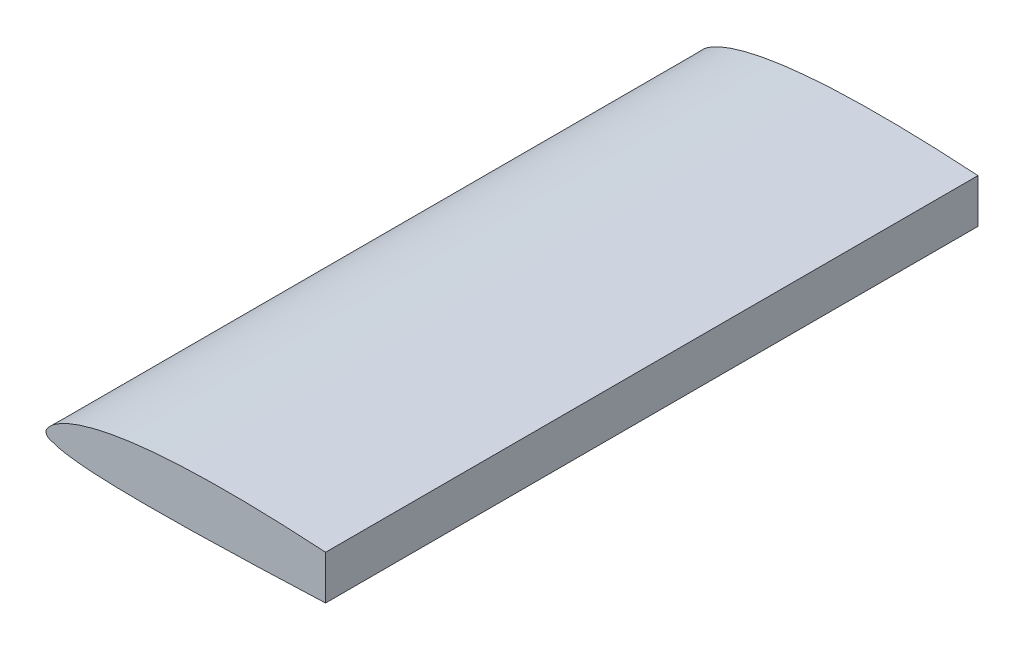
SolidWorks part; units mm, degrees
ref_plane "Front Plane" through (0, 0, 0) normal (0, 0, 1) x (1, 0, 0)
ref_plane "Top Plane" through (0, 0, 0) normal (0, 1, 0) x (1, 0, 0)
ref_plane "Right Plane" through (0, 0, 0) normal (1, 0, 0) x (0, 0, -1)
curve "Curve1"
  spline degree 3 poles (152.4, 0, 0) (152.2328, 0.0185, 0) (151.5718, 0.0917, 0) (150.114, 0.2839, 0) (147.7494, 0.6387, 0) (144.5559, 1.1702, 0) (140.6154, 1.8591, 0) (136.0078, 2.6715, 0) (130.8064, 3.5628, 0) (125.0738, 4.4862, 0) (118.8647, 5.3978, 0) (112.2333, 6.273, 0) (105.2435, 7.1061, 0) (97.9697, 7.8893, 0) (90.4927, 8.6067, 0) (82.8953, 9.2407, 0) (75.2587, 9.7775, 0) (67.6629, 10.1988, 0) (60.1868, 10.4917, 0) (52.9059, 10.6451, 0) (45.8917, 10.6446, 0) (39.2107, 10.4862, 0) (32.9233, 10.1644, 0) (27.0837, 9.6709, 0) (21.7372, 9.0165, 0) (16.9243, 8.2041, 0) (12.6763, 7.2498, 0) (9.0198, 6.1745, 0) (5.9657, 5.002, 0) (3.544, 3.7699, 0) (1.7048, 2.5315, 0) (0.5752, 1.3447, 0) (-0.1707, 0.2031, 0) (0.3376, -1.0018, 0) (1.7929, -1.5467, 0) (3.7942, -2.1772, 0) (6.6434, -2.6439, 0) (10.2161, -3.042, 0) (14.5301, -3.3199, 0) (19.534, -3.4977, 0) (25.1869, -3.5776, 0) (31.4286, -3.5738, 0) (38.1919, -3.4966, 0) (45.4016, -3.3493, 0) (52.9784, -3.1418, 0) (60.8387, -2.8853, 0) (68.895, -2.5879, 0) (77.0574, -2.2589, 0) (85.235, -1.9077, 0) (93.3354, -1.5502, 0) (101.266, -1.1955, 0) (108.9342, -0.8624, 0) (116.2465, -0.5575, 0) (123.1102, -0.3069, 0) (129.4317, -0.1079, 0) (135.1235, 0.028, 0) (140.1036, 0.1089, 0) (144.2994, 0.1399, 0) (147.6448, 0.1242, 0) (150.0834, 0.0865, 0) (151.3998, 0.0403, 0) (151.8986, 0.0229, 0) knots 0 0 0 0 0.001635 0.006466 0.014297 0.024884 0.037944 0.053194 0.070377 0.089257 0.109652 0.131396 0.154295 0.178097 0.202531 0.227329 0.252226 0.276966 0.301297 0.324972 0.347773 0.369494 0.389947 0.408979 0.426466 0.442307 0.456421 0.468774 0.479345 0.488156 0.495223 0.500608 0.504417 0.507344 0.511893 0.518766 0.528062 0.53975 0.553782 0.570059 0.588441 0.608748 0.63075 0.654208 0.678865 0.704451 0.730678 0.757254 0.783883 0.810266 0.836095 0.861073 0.884897 0.907258 0.927856 0.946395 0.962618 0.976286 0.987193 0.995147 1 1 1 1
sketch "Sketch1" plane through (0, 0, 0) normal (0, 0, 1) x (1, 0, 0)
  line L0 (151.8986, 0.0229) -> (152.4, 0)
  line L2 (0, 0) -> (0, 1.9929) construction
  spline S0 degree 3 poles (-13.6531, -1992.4593) (197.8364, 10.3076) (173.4363, -2.7909) (150.114, 0.2839) (147.7494, 0.6387) (144.5559, 1.1702) (140.6154, 1.8591) (136.0078, 2.6715) (130.8064, 3.5628) (125.0738, 4.4862) (118.8647, 5.3978) (112.2333, 6.273) (105.2435, 7.1061) (97.9697, 7.8893) (90.4927, 8.6067) (82.8953, 9.2407) (75.2587, 9.7775) (67.6629, 10.1988) (60.1868, 10.4917) (52.9059, 10.6451) (45.8917, 10.6446) (39.2107, 10.4862) (32.9233, 10.1644) (27.0837, 9.6709) (21.7372, 9.0165) (16.9243, 8.2041) (12.6763, 7.2498) (9.0198, 6.1745) (5.9657, 5.002) (3.544, 3.7699) (1.7048, 2.5315) (0.5752, 1.3447) (-0.1707, 0.2031) (0.3376, -1.0018) (1.7929, -1.5467) (3.7942, -2.1772) (6.6434, -2.6439) (10.2161, -3.042) (14.5301, -3.3199) (19.534, -3.4977) (25.1869, -3.5776) (31.4286, -3.5738) (38.1919, -3.4966) (45.4016, -3.3493) (52.9784, -3.1418) (60.8387, -2.8853) (68.895, -2.5879) (77.0574, -2.2589) (85.235, -1.9077) (93.3354, -1.5502) (101.266, -1.1955) (108.9342, -0.8624) (116.2465, -0.5575) (123.1102, -0.3069) (129.4317, -0.1079) (135.1235, 0.028) (140.1036, 0.1089) (144.2994, 0.1399) (147.6448, 0.1242) (190.703, -0.5421) (231.9179, -27.3192) (328.7943, 1990.768) knots -0.214418 -0.214418 -0.214418 -0.214418 0.001635 0.006466 0.014297 0.024884 0.037944 0.053194 0.070377 0.089257 0.109652 0.131396 0.154295 0.178097 0.202531 0.227329 0.252226 0.276966 0.301297 0.324972 0.347773 0.369494 0.389947 0.408979 0.426466 0.442307 0.456421 0.468774 0.479345 0.488156 0.495223 0.500608 0.504417 0.507344 0.511893 0.518766 0.528062 0.53975 0.553782 0.570059 0.588441 0.608748 0.63075 0.654208 0.678865 0.704451 0.730678 0.757254 0.783883 0.810266 0.836095 0.861073 0.884897 0.907258 0.927856 0.946395 0.962618 0.976286 0.987193 0.995147 1.394988 1.394988 1.394988 1.394988 only from (152.4, 0) to (151.8986, 0.0229) construction
  spline S1 degree 3 poles (152.4, 0) (152.2328, 0.0185) (151.5718, 0.0917) (150.114, 0.2839) (147.7494, 0.6387) (144.5559, 1.1702) (140.6154, 1.8591) (136.0078, 2.6715) (130.8064, 3.5628) (125.0738, 4.4862) (118.8647, 5.3978) (112.2333, 6.273) (105.2435, 7.1061) (97.9697, 7.8893) (90.4927, 8.6067) (82.8953, 9.2407) (75.2587, 9.7775) (67.6629, 10.1988) (60.1868, 10.4917) (52.9059, 10.6451) (45.8917, 10.6446) (39.2107, 10.4862) (32.9233, 10.1644) (27.0837, 9.6709) (21.7372, 9.0165) (16.9243, 8.2041) (12.6763, 7.2498) (9.0198, 6.1745) (5.9657, 5.002) (3.544, 3.7699) (1.7048, 2.5315) (0.5752, 1.3447) (-0.1707, 0.2031) (0.3376, -1.0018) (1.7929, -1.5467) (3.7942, -2.1772) (6.6434, -2.6439) (10.2161, -3.042) (14.5301, -3.3199) (19.534, -3.4977) (25.1869, -3.5776) (31.4286, -3.5738) (38.1919, -3.4966) (45.4016, -3.3493) (52.9784, -3.1418) (60.8387, -2.8853) (68.895, -2.5879) (77.0574, -2.2589) (85.235, -1.9077) (93.3354, -1.5502) (101.266, -1.1955) (108.9342, -0.8624) (116.2465, -0.5575) (123.1102, -0.3069) (129.4317, -0.1079) (135.1235, 0.028) (140.1036, 0.1089) (144.2994, 0.1399) (147.6448, 0.1242) (150.0834, 0.0865) (151.3998, 0.0403) (151.8986, 0.0229) knots 0 0 0 0 0.001635 0.006466 0.014297 0.024884 0.037944 0.053194 0.070377 0.089257 0.109652 0.131396 0.154295 0.178097 0.202531 0.227329 0.252226 0.276966 0.301297 0.324972 0.347773 0.369494 0.389947 0.408979 0.426466 0.442307 0.456421 0.468774 0.479345 0.488156 0.495223 0.500608 0.504417 0.507344 0.511893 0.518766 0.528062 0.53975 0.553782 0.570059 0.588441 0.608748 0.63075 0.654208 0.678865 0.704451 0.730678 0.757254 0.783883 0.810266 0.836095 0.861073 0.884897 0.907258 0.927856 0.946395 0.962618 0.976286 0.987193 0.995147 1 1 1 1
extrude "Boss-Extrude1" add sketch "Sketch1" along normal blind 177.8
sketch "Sketch3" plane through (0, 0, 177.8) normal (0, 0, 1) x (1, 0, 0)
  line L0 (76.2, 9.6986) -> (76.2, -2.2909)
  line L1 (0, 0) -> (0, 3.7038) construction
  line L2 (76.2, 3.7038) -> (0, 3.7038) construction
  line L4 (151.8986, 0.0229) -> (152.4, 0)
  line L5 (151.8986, 0.0229) -> (152.4, 0)
  spline S0 degree 3 poles (152.4, 0) (152.2328, 0.0185) (151.5718, 0.0917) (150.114, 0.2839) (147.7494, 0.6387) (144.5559, 1.1702) (140.6154, 1.8591) (136.0078, 2.6715) (130.8064, 3.5628) (125.0738, 4.4862) (118.8647, 5.3978) (112.2333, 6.273) (105.2435, 7.1061) (97.9697, 7.8893) (90.4927, 8.6067) (82.8953, 9.2407) (75.2587, 9.7775) (67.6629, 10.1988) (60.1868, 10.4917) (52.9059, 10.6451) (45.8917, 10.6446) (39.2107, 10.4862) (32.9233, 10.1644) (27.0837, 9.6709) (21.7372, 9.0165) (16.9243, 8.2041) (12.6763, 7.2498) (9.0198, 6.1745) (5.9657, 5.002) (3.544, 3.7699) (1.7048, 2.5315) (0.5752, 1.3447) (-0.1707, 0.2031) (0.3376, -1.0018) (1.7929, -1.5467) (3.7942, -2.1772) (6.6434, -2.6439) (10.2161, -3.042) (14.5301, -3.3199) (19.534, -3.4977) (25.1869, -3.5776) (31.4286, -3.5738) (38.1919, -3.4966) (45.4016, -3.3493) (52.9784, -3.1418) (60.8387, -2.8853) (68.895, -2.5879) (77.0574, -2.2589) (85.235, -1.9077) (93.3354, -1.5502) (101.266, -1.1955) (108.9342, -0.8624) (116.2465, -0.5575) (123.1102, -0.3069) (129.4317, -0.1079) (135.1235, 0.028) (140.1036, 0.1089) (144.2994, 0.1399) (147.6448, 0.1242) (150.0834, 0.0865) (151.3998, 0.0403) (151.8986, 0.0229) knots 0 0 0 0 0.001635 0.006466 0.014297 0.024884 0.037944 0.053194 0.070377 0.089257 0.109652 0.131396 0.154295 0.178097 0.202531 0.227329 0.252226 0.276966 0.301297 0.324972 0.347773 0.369494 0.389947 0.408979 0.426466 0.442307 0.456421 0.468774 0.479345 0.488156 0.495223 0.500608 0.504417 0.507344 0.511893 0.518766 0.528062 0.53975 0.553782 0.570059 0.588441 0.608748 0.63075 0.654208 0.678865 0.704451 0.730678 0.757254 0.783883 0.810266 0.836095 0.861073 0.884897 0.907258 0.927856 0.946395 0.962618 0.976286 0.987193 0.995147 1 1 1 1 construction
  spline S1 degree 3 poles (152.4, 0) (152.2328, 0.0185) (151.5718, 0.0917) (150.114, 0.2839) (147.7494, 0.6387) (144.5559, 1.1702) (140.6154, 1.8591) (136.0078, 2.6715) (130.8064, 3.5628) (125.0738, 4.4862) (118.8647, 5.3978) (112.2333, 6.273) (105.2435, 7.1061) (97.9697, 7.8893) (90.4927, 8.6067) (82.8953, 9.2407) (75.2587, 9.7775) (67.6629, 10.1988) (60.1868, 10.4917) (52.9059, 10.6451) (45.8917, 10.6446) (39.2107, 10.4862) (32.9233, 10.1644) (27.0837, 9.6709) (21.7372, 9.0165) (16.9243, 8.2041) (12.6763, 7.2498) (9.0198, 6.1745) (5.9657, 5.002) (3.544, 3.7699) (1.7048, 2.5315) (0.5752, 1.3447) (-0.1707, 0.2031) (0.3376, -1.0018) (1.7929, -1.5467) (3.7942, -2.1772) (6.6434, -2.6439) (10.2161, -3.042) (14.5301, -3.3199) (19.534, -3.4977) (25.1869, -3.5776) (31.4286, -3.5738) (38.1919, -3.4966) (45.4016, -3.3493) (52.9784, -3.1418) (60.8387, -2.8853) (68.895, -2.5879) (77.0574, -2.2589) (85.235, -1.9077) (93.3354, -1.5502) (101.266, -1.1955) (108.9342, -0.8624) (116.2465, -0.5575) (123.1102, -0.3069) (129.4317, -0.1079) (135.1235, 0.028) (140.1036, 0.1089) (144.2994, 0.1399) (147.6448, 0.1242) (150.0834, 0.0865) (151.3998, 0.0403) (151.8986, 0.0229) knots 0 0 0 0 0.001635 0.006466 0.014297 0.024884 0.037944 0.053194 0.070377 0.089257 0.109652 0.131396 0.154295 0.178097 0.202531 0.227329 0.252226 0.276966 0.301297 0.324972 0.347773 0.369494 0.389947 0.408979 0.426466 0.442307 0.456421 0.468774 0.479345 0.488156 0.495223 0.500608 0.504417 0.507344 0.511893 0.518766 0.528062 0.53975 0.553782 0.570059 0.588441 0.608748 0.63075 0.654208 0.678865 0.704451 0.730678 0.757254 0.783883 0.810266 0.836095 0.861073 0.884897 0.907258 0.927856 0.946395 0.962618 0.976286 0.987193 0.995147 1 1 1 1 construction
  spline S3 degree 3 poles (-120.0863, -2986.5223) (204.7313, 14.3063) (176.6016, -3.2082) (150.114, 0.2839) (147.7494, 0.6387) (144.5559, 1.1702) (140.6154, 1.8591) (136.0078, 2.6715) (130.8064, 3.5628) (125.0738, 4.4862) (118.8647, 5.3978) (112.2333, 6.273) (105.2435, 7.1061) (97.9697, 7.8893) (90.4927, 8.6067) (82.8953, 9.2407) (75.2587, 9.7775) (67.6629, 10.1988) (60.1868, 10.4917) (52.9059, 10.6451) (45.8917, 10.6446) (39.2107, 10.4862) (32.9233, 10.1644) (27.0837, 9.6709) (21.7372, 9.0165) (16.9243, 8.2041) (12.6763, 7.2498) (9.0198, 6.1745) (5.9657, 5.002) (3.544, 3.7699) (1.7048, 2.5315) (0.5752, 1.3447) (-0.1707, 0.2031) (0.3376, -1.0018) (1.7929, -1.5467) (3.7942, -2.1772) (6.6434, -2.6439) (10.2161, -3.042) (14.5301, -3.3199) (19.534, -3.4977) (25.1869, -3.5776) (31.4286, -3.5738) (38.1919, -3.4966) (45.4016, -3.3493) (52.9784, -3.1418) (60.8387, -2.8853) (68.895, -2.5879) (77.0574, -2.2589) (85.235, -1.9077) (93.3354, -1.5502) (101.266, -1.1955) (108.9342, -0.8624) (116.2465, -0.5575) (123.1102, -0.3069) (129.4317, -0.1079) (135.1235, 0.028) (140.1036, 0.1089) (144.2994, 0.1399) (147.6448, 0.1242) (196.5916, -0.6332) (243.4783, -35.3543) (374.0575, 2989.6631) knots -0.245458 -0.245458 -0.245458 -0.245458 0.001635 0.006466 0.014297 0.024884 0.037944 0.053194 0.070377 0.089257 0.109652 0.131396 0.154295 0.178097 0.202531 0.227329 0.252226 0.276966 0.301297 0.324972 0.347773 0.369494 0.389947 0.408979 0.426466 0.442307 0.456421 0.468774 0.479345 0.488156 0.495223 0.500608 0.504417 0.507344 0.511893 0.518766 0.528062 0.53975 0.553782 0.570059 0.588441 0.608748 0.63075 0.654208 0.678865 0.704451 0.730678 0.757254 0.783883 0.810266 0.836095 0.861073 0.884897 0.907258 0.927856 0.946395 0.962618 0.976286 0.987193 0.995147 1.45225 1.45225 1.45225 1.45225 only from (152.4, 0) to (151.8986, 0.0229)
  spline S5 degree 3 poles (152.4, 0) (152.2328, 0.0185) (151.5718, 0.0917) (150.114, 0.2839) (147.7494, 0.6387) (144.5559, 1.1702) (140.6154, 1.8591) (136.0078, 2.6715) (130.8064, 3.5628) (125.0738, 4.4862) (118.8647, 5.3978) (112.2333, 6.273) (105.2435, 7.1061) (97.9697, 7.8893) (90.4927, 8.6067) (82.8953, 9.2407) (75.2587, 9.7775) (67.6629, 10.1988) (60.1868, 10.4917) (52.9059, 10.6451) (45.8917, 10.6446) (39.2107, 10.4862) (32.9233, 10.1644) (27.0837, 9.6709) (21.7372, 9.0165) (16.9243, 8.2041) (12.6763, 7.2498) (9.0198, 6.1745) (5.9657, 5.002) (3.544, 3.7699) (1.7048, 2.5315) (0.5752, 1.3447) (-0.1707, 0.2031) (0.3376, -1.0018) (1.7929, -1.5467) (3.7942, -2.1772) (6.6434, -2.6439) (10.2161, -3.042) (14.5301, -3.3199) (19.534, -3.4977) (25.1869, -3.5776) (31.4286, -3.5738) (38.1919, -3.4966) (45.4016, -3.3493) (52.9784, -3.1418) (60.8387, -2.8853) (68.895, -2.5879) (77.0574, -2.2589) (85.235, -1.9077) (93.3354, -1.5502) (101.266, -1.1955) (108.9342, -0.8624) (116.2465, -0.5575) (123.1102, -0.3069) (129.4317, -0.1079) (135.1235, 0.028) (140.1036, 0.1089) (144.2994, 0.1399) (147.6448, 0.1242) (150.0834, 0.0865) (151.3998, 0.0403) (151.8986, 0.0229) knots 0 0 0 0 0.001635 0.006466 0.014297 0.024884 0.037944 0.053194 0.070377 0.089257 0.109652 0.131396 0.154295 0.178097 0.202531 0.227329 0.252226 0.276966 0.301297 0.324972 0.347773 0.369494 0.389947 0.408979 0.426466 0.442307 0.456421 0.468774 0.479345 0.488156 0.495223 0.500608 0.504417 0.507344 0.511893 0.518766 0.528062 0.53975 0.553782 0.570059 0.588441 0.608748 0.63075 0.654208 0.678865 0.704451 0.730678 0.757254 0.783883 0.810266 0.836095 0.861073 0.884897 0.907258 0.927856 0.946395 0.962618 0.976286 0.987193 0.995147 1 1 1 1
  spline M6 degree 3 poles (152.4, 0) (152.2328, 0.0185) (151.5718, 0.0917) (150.114, 0.2839) (147.7494, 0.6387) (144.5559, 1.1702) (140.6154, 1.8591) (136.0078, 2.6715) (130.8064, 3.5628) (125.0738, 4.4862) (118.8647, 5.3978) (112.2333, 6.273) (105.2435, 7.1061) (97.9697, 7.8893) (90.4927, 8.6067) (82.8953, 9.2407) (75.2587, 9.7775) (67.6629, 10.1988) (60.1868, 10.4917) (52.9059, 10.6451) (45.8917, 10.6446) (39.2107, 10.4862) (32.9233, 10.1644) (27.0837, 9.6709) (21.7372, 9.0165) (16.9243, 8.2041) (12.6763, 7.2498) (9.0198, 6.1745) (5.9657, 5.002) (3.544, 3.7699) (1.7048, 2.5315) (0.5752, 1.3447) (-0.1707, 0.2031) (0.3376, -1.0018) (1.7929, -1.5467) (3.7942, -2.1772) (6.6434, -2.6439) (10.2161, -3.042) (14.5301, -3.3199) (19.534, -3.4977) (25.1869, -3.5776) (31.4286, -3.5738) (38.1919, -3.4966) (45.4016, -3.3493) (52.9784, -3.1418) (60.8387, -2.8853) (68.895, -2.5879) (77.0574, -2.2589) (85.235, -1.9077) (93.3354, -1.5502) (101.266, -1.1955) (108.9342, -0.8624) (116.2465, -0.5575) (123.1102, -0.3069) (129.4317, -0.1079) (135.1235, 0.028) (140.1036, 0.1089) (144.2994, 0.1399) (147.6448, 0.1242) (150.0834, 0.0865) (151.3998, 0.0403) (151.8986, 0.0229) knots 0 0 0 0 0.001635 0.006466 0.014297 0.024884 0.037944 0.053194 0.070377 0.089257 0.109652 0.131396 0.154295 0.178097 0.202531 0.227329 0.252226 0.276966 0.301297 0.324972 0.347773 0.369494 0.389947 0.408979 0.426466 0.442307 0.456421 0.468774 0.479345 0.488156 0.495223 0.500608 0.504417 0.507344 0.511893 0.518766 0.528062 0.53975 0.553782 0.570059 0.588441 0.608748 0.63075 0.654208 0.678865 0.704451 0.730678 0.757254 0.783883 0.810266 0.836095 0.861073 0.884897 0.907258 0.927856 0.946395 0.962618 0.976286 0.987193 0.995147 1 1 1 1
  line M12 (151.8986, 0.0229) -> (152.4, 0)
  dimension "D2" = 76.2
  dimension "D1" = 0
extrude "Cut-Extrude1" cut sketch "Sketch3" against normal up to next contours L0 M6 M12
